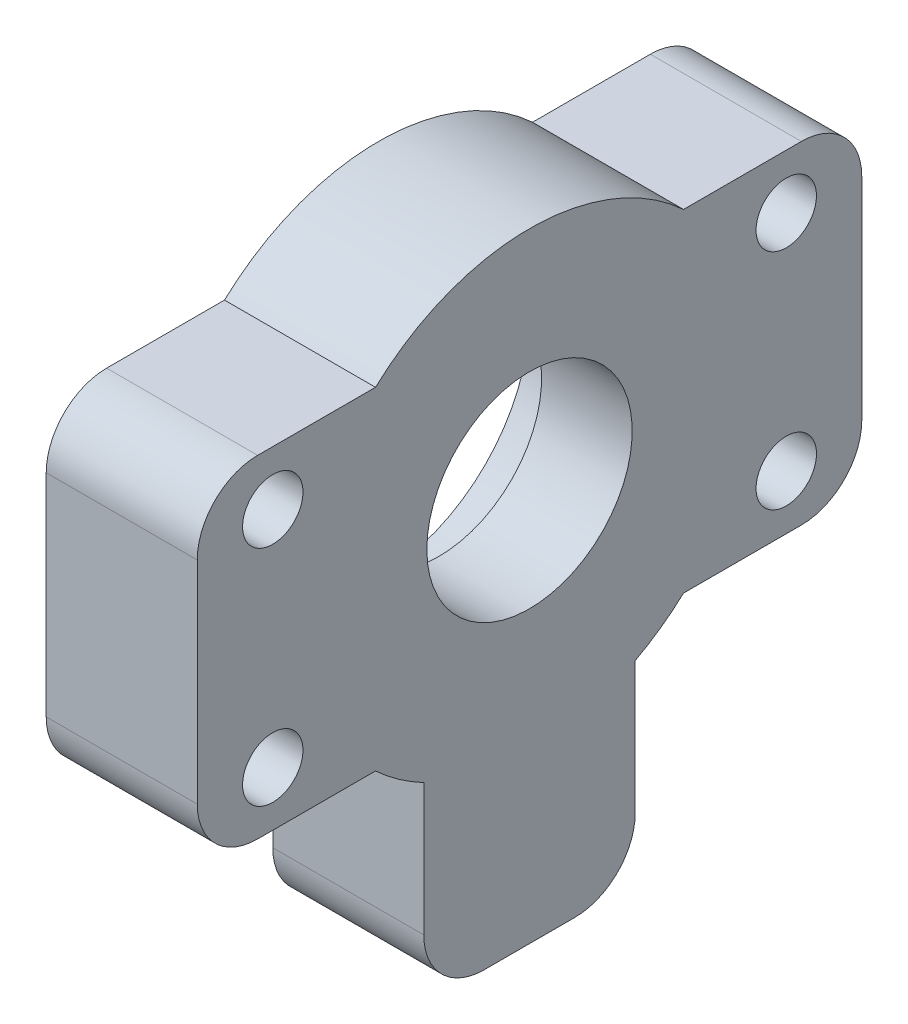
SolidWorks part; units mm, degrees
ref_plane "前视基准面" through (0, 0, 0) normal (0, 0, 1) x (1, 0, 0)
ref_plane "上视基准面" through (0, 0, 0) normal (0, 1, 0) x (1, 0, 0)
ref_plane "右视基准面" through (0, 0, 0) normal (1, 0, 0) x (0, 0, -1)
sketch "草图1" plane through (0, 0, 0) normal (1, 0, 0) x (0, 0, -1)
  circle A0 centre (0, 0) radius 7.5
  dimension "D1" = 15
extrude "凸台-拉伸1" add sketch "草图1" along normal blind 5
sketch "草图2" plane through (0, 0, 0) normal (-1, 0, 0) x (0, 0, 1)
  circle A0 centre (0, 0) radius 5
  dimension "D1" = 10
extrude "切除-拉伸1" cut sketch "草图2" against normal blind 2
sketch "草图3" plane through (2, 0, 0) normal (-1, 0, 0) x (0, 0, 1)
  circle A0 centre (0, 0) radius 3.4
  dimension "D1" = 6.8
extrude "切除-拉伸2" cut sketch "草图3" against normal through all
sketch "草图4" plane through (0, 0, 0) normal (-1, 0, 0) x (0, 0, 1)
  line L1 (5, 5.5) -> (11, 5.5)
  line L2 (5, 5.5) -> (5, -5.5)
  line L3 (5, -5.5) -> (11, -5.5)
  line L4 (11, 5.5) -> (11, -5.5)
  line L5 (-11, 5.5) -> (-5, 5.5)
  line L6 (-11, 5.5) -> (-11, -5.5)
  line L7 (-11, -5.5) -> (-5, -5.5)
  line L8 (-5, 5.5) -> (-5, -5.5)
  circle A0 centre (0, 0) radius 7.5 construction
  dimension "D1" = 6
  dimension "D2" = 11
  dimension "D3" = 5.5
  dimension "D4" = 5
  dimension "D5" = 6
  dimension "D6" = 11
  dimension "D7" = 5.5
  dimension "D8" = 5
extrude "凸台-拉伸2" add sketch "草图4" against normal blind 5
sketch "草图6" plane through (0, 0, 0) normal (-1, 0, 0) x (0, 0, 1)
  line L1 (11, -5.5) -> (11, 5.5) construction
  line L3 (11, 5.5) -> (5.099, 5.5) construction
  line L4 (8, 2.65) -> (8, -2.65) construction
  line L5 (8, 2.65) -> (8, -2.65)
  arc A0 (8, -2.65) -> (8, 2.65) centre (8, 0) ccw
  dimension "D1" = 5.3
  dimension "D4" = 3
  dimension "D6" = 5.5
revolve "切除-旋转1" cut sketch "草图6" angle 360 about L4
sketch "草图7" plane through (0, 0, 0) normal (-1, 0, 0) x (0, 0, 1)
  line L0 (-11, 5.5) -> (-11, -5.5) construction
  line L1 (-5.099, 5.5) -> (-11, 5.5) construction
  line L2 (-8, 2.65) -> (-8, -2.65)
  arc A0 (-8, -2.65) -> (-8, 2.65) centre (-8, 0) ccw
  dimension "D1" = 5.3
  dimension "D2" = 3
  dimension "D3" = 5.5
revolve "切除-旋转2" cut sketch "草图7" angle 360 about L2
fillet "圆角1" radius 2 4 edges at (2.5, 5.5, 11) (2.5, 5.5, -11) (2.5, -5.5, -11) (2.5, -5.5, 11)
sketch "草图8" plane through (0, 0, 0) normal (-1, 0, 0) x (0, 0, 1)
  line L0 (11, -3.5) -> (11, 3.5) construction
  line L1 (5.099, -5.5) -> (9, -5.5) construction
  line L2 (11, 0) -> (-11, 0) construction
  line L3 (-11, 3.5) -> (-11, -3.5) construction
  line L4 (0, 7.5) -> (0, -7.5) construction
  circle A0 centre (8.5, -3.7) radius 1
  arc A1 (5.099, 5.5) -> (-5.099, 5.5) centre (0, 0) ccw construction
  arc A2 (-5.099, -5.5) -> (5.099, -5.5) centre (0, 0) ccw construction
  circle A3 centre (8.5, 3.7) radius 1
  circle A4 centre (-8.5, -3.7) radius 1
  circle A5 centre (-8.5, 3.7) radius 1
  dimension "D1" = 2
  dimension "D2" = 2.5
  dimension "D3" = 1.8
extrude "切除-拉伸4" cut sketch "草图8" against normal through all
sketch "草图9" plane through (5, 0, 0) normal (1, 0, 0) x (0, 0, -1)
  line L1 (3.5, -5.5) -> (-3.5, -5.5)
  line L2 (3.5, -5.5) -> (3.5, -13)
  line L3 (3.5, -13) -> (-3.5, -13)
  line L4 (-3.5, -5.5) -> (-3.5, -13)
  circle A0 centre (0, 0) radius 3.4 construction
  point P5 (0, 0)
  point P6 (0, 0)
  dimension "D1" = 7.5
  dimension "D2" = 7
  dimension "D3" = 3.5
  dimension "D4" = 5.5
extrude "凸台-拉伸3" add sketch "草图9" against normal blind 5
sketch "草图10" plane through (0, 0, 0) normal (-1, 0, 0) x (0, 0, 1)
  line L0 (3.5, -13) -> (-3.5, -13) construction
  line L1 (3.5, -6.6332) -> (3.5, -13) construction
  line L2 (0, -7.35) -> (0, -12.65)
  arc A0 (0, -7.35) -> (0, -12.65) centre (0, -10) ccw
  dimension "D1" = 5.3
  dimension "D2" = 3
  dimension "D3" = 3.5
revolve "切除-旋转3" cut sketch "草图10" angle 360 about L2
fillet "圆角2" radius 2 2 edges at (2.5, -13, -3.5) (2.5, -13, 3.5)
